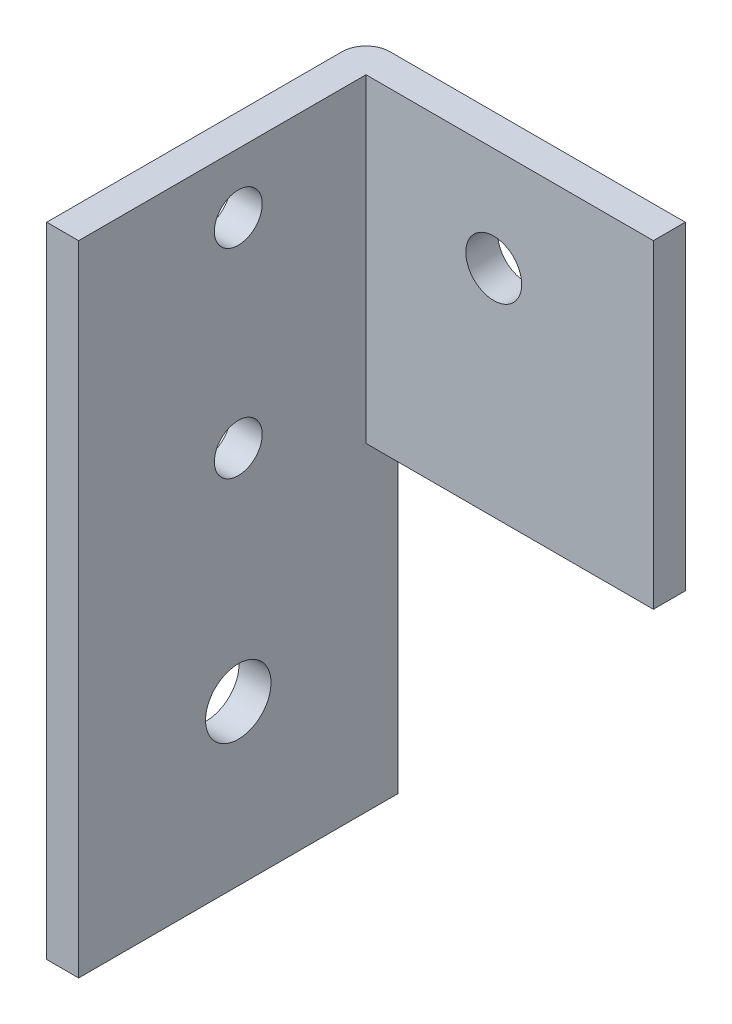
SolidWorks part; units mm, degrees
ref_plane "Front Plane" through (0, 0, 0) normal (0, 0, 1) x (1, 0, 0)
ref_plane "Top Plane" through (0, 0, 0) normal (0, 1, 0) x (1, 0, 0)
ref_plane "Right Plane" through (0, 0, 0) normal (1, 0, 0) x (0, 0, -1)
sketch "Sketch1" plane through (0, 0, 0) normal (0, 1, 0) x (1, 0, 0)
  line L0 (-22.659, -16.8786) -> (-22.659, 20.1214)
  line L1 (-19.659, 23.1214) -> (17.341, 23.1214)
  arc A0 (-22.659, 20.1214) -> (-19.659, 23.1214) centre (-19.659, 20.1214) cw
  point P5 (-22.659, 23.1214)
  dimension "D3" = 3
  dimension "D1" = 40
  dimension "D2" = 40
extrude "Extrude-Thin1" add sketch "Sketch1" along normal blind 80 thin
sketch "Sketch4" plane through (0, 0, -23.1214) normal (0, 0, -1) x (-1, 0, 0)
  line L0 (-17.341, 80) -> (-17.341, 0) construction
  line L1 (19.659, 80) -> (-17.341, 80) construction
  line L2 (19.659, 0) -> (-17.341, 0) construction
  circle A0 centre (2.659, 60) radius 2
  circle A1 centre (2.659, 20) radius 4.1
  dimension "D1" = 4
  dimension "D2" = 8.2
  dimension "D3" = 20
  dimension "D4" = 20
  dimension "D5" = 20
  dimension "D6" = 20
sketch "Sketch5" plane through (-22.659, 0, 0) normal (-1, 0, 0) x (0, 0, 1)
  line L1 (16.8786, 80) -> (16.8786, 0) construction
  line L3 (16.8786, 0) -> (-20.1214, 0) construction
  circle A1 centre (-3.1214, 20) radius 4.1
  circle A2 centre (-3.1214, 47.5) radius 3
  circle A3 centre (-3.1214, 72.5) radius 3
  dimension "D1" = 6
  dimension "D2" = 6
  dimension "D4" = 20
  dimension "D5" = 20
extrude "Cut-Extrude2" cut sketch "Sketch5" against normal blind 10
sketch "Sketch6" plane through (0, 0, -23.1214) normal (0, 0, -1) x (-1, 0, 0)
  line L1 (-38.7536, 40) -> (18.659, 40)
  line L2 (-38.7536, 40) -> (-38.7536, 0)
  line L3 (-38.7536, 0) -> (18.659, 0)
  line L4 (18.659, 40) -> (18.659, 0)
  line L5 (-38.7536, 40) -> (18.659, 0) construction
  line L6 (-38.7536, 0) -> (18.659, 40) construction
  line L7 (19.659, 0) -> (-17.341, 0) construction
  line L8 (18.659, 80) -> (18.659, 0) construction
  point P0 (-10.0473, 20)
  dimension "D1" = 40
  dimension "D2" = 0
  dimension "D3" = 0
extrude "Cut-Extrude3" cut sketch "Sketch6" against normal blind 10
hole_wizard "M8x1.0 Tapped Hole3" positions "Sketch8" profile "Sketch7" tap size "M8x1.0" standard "ANSI Metric" end condition through all
sketch "Sketch8" plane through (0, 0, -23.1214) normal (0, 0, -1) x (-1, 0, 0)
  line L0 (-17.341, 80) -> (-17.341, 40) construction
  line L1 (19.659, 80) -> (-17.341, 80) construction
  point P0 (2.659, 67)
  dimension "D1" = 20
  dimension "D2" = 13
sketch "Sketch7" plane through (-2.659, 67, -23.1214) normal (1, 0, 0) x (0, 1, 0)
  line L0 (0, 0) -> (0, 40)
  line L1 (0, 40) -> (3.5, 40)
  line L2 (3.5, 40) -> (3.5, 0)
  line L5 (3.5, 0) -> (0, 0)
  line L11 (0, -6.35) -> (0, 107.95) construction
  dimension "Thru Tap Drill Dia." = 7
  dimension "Thru Tap Drill Depth" = 40
cosmetic thread "Hole Thread1" parameters "D2"=8
